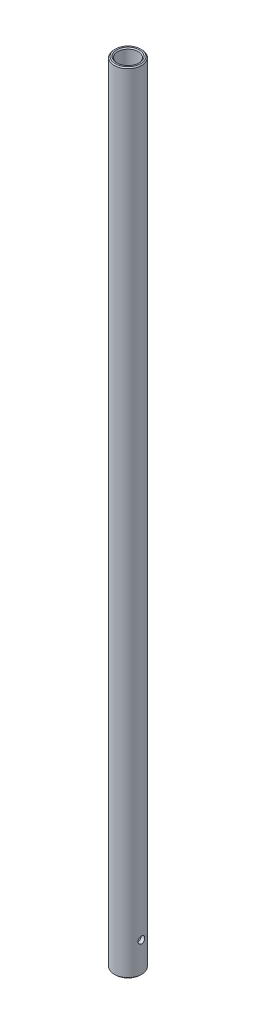
SolidWorks part; units mm, degrees
material "AISI 304"
ref_plane "Спереди" through (0, 0, 0) normal (0, 0, 1) x (1, 0, 0)
ref_plane "Сверху" through (0, 0, 0) normal (0, 1, 0) x (1, 0, 0)
ref_plane "Справа" through (0, 0, 0) normal (1, 0, 0) x (0, 0, -1)
other "Configuration Table"
sketch "Эскиз1" plane through (0, 0, 0) normal (0, 1, 0) x (1, 0, 0)
  circle A0 centre (0, 0) radius 4
  circle A1 centre (0, 0) radius 3
  dimension "D1" = 8
  dimension "D2" = 6
extrude "Бобышка-Вытянуть1" add sketch "Эскиз1" along normal blind 230
chamfer "Фаска1" distance 0.3 angle 45 4 edges at (0, 230, 3) (0, 0, 3) (0, 0, 4) (0, 230, 4)
sketch "Эскиз2" plane through (0, 0, 0) normal (1, 0, 0) x (0, 0, -1)
  circle A0 centre (0, 9) radius 1 construction
  circle A1 centre (0, 9) radius 1
extrude "Вырез-Вытянуть1" cut sketch "Эскиз2" against normal through all both and the other way through all
